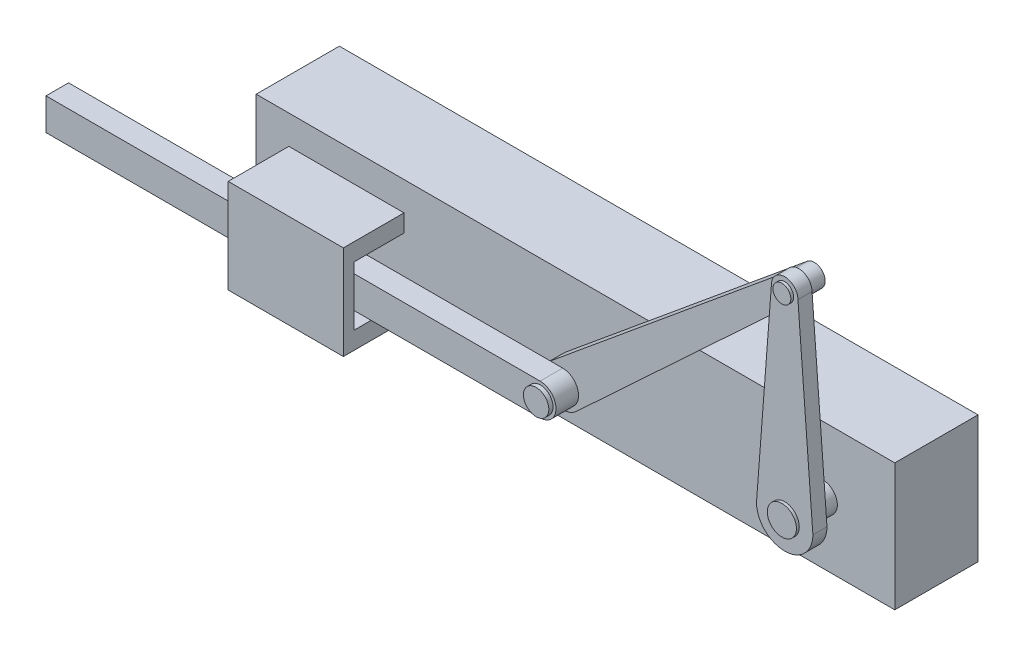
SolidWorks part; units mm, degrees
ref_plane "前视基准面" through (0, 0, 0) normal (0, 0, 1) x (1, 0, 0)
ref_plane "上视基准面" through (0, 0, 0) normal (0, 1, 0) x (1, 0, 0)
ref_plane "右视基准面" through (0, 0, 0) normal (1, 0, 0) x (0, 0, -1)
sketch "草图1" plane through (0, 0, 0) normal (0, 0, 1) x (1, 0, 0)
  line L1 (-43.2595, 0) -> (71.7598, 0)
  line L2 (-43.2595, 0) -> (-43.2595, -22.9274)
  line L3 (-43.2595, -22.9274) -> (71.7598, -22.9274)
  line L4 (71.7598, 0) -> (71.7598, -22.9274)
extrude "凸台-拉伸1" add sketch "草图1" along normal blind 14.986
sketch "草图2" plane through (0, 0, 14.986) normal (0, 0, 1) x (1, 0, 0)
  circle A0 centre (58.7859, -11.7435) radius 2.6281
extrude "凸台-拉伸2" add sketch "草图2" along normal blind 7.366
ref_plane "基准面1" through (0, 0, 21.844) normal (0, 0, 1) x (1, 0, 0)
sketch "草图3" plane through (0, 0, 21.844) normal (0, 0, 1) x (1, 0, 0)
  line L0 (53.7065, -11.7435) -> (56.4009, 23.5958)
  line L1 (63.8654, -11.7435) -> (61.171, 23.5958)
  arc A0 (53.7652, -10.9734) -> (63.8067, -10.9734) centre (58.7859, -11.7435) ccw
  arc A1 (61.171, 23.5958) -> (56.4009, 23.5958) centre (58.7859, 23.5958) ccw
extrude "凸台-拉伸3" add sketch "草图3" against normal blind 2.54 contours L1 A1 L0 A0
sketch "草图5" plane through (0, 0, 19.304) normal (0, 0, -1) x (-1, 0, 0)
  line L0 (-57.5365, 25.1089) -> (-13.9492, -10.8833)
  line L1 (-18.7214, -16.3288) -> (-60.122, 22.1586)
  arc A0 (-57.5365, 25.1089) -> (-60.122, 22.1586) centre (-58.7859, 23.5958) ccw
  arc A1 (-18.7214, -16.3288) -> (-13.9492, -10.8833) centre (-16.2554, -13.6761) ccw
extrude "凸台-拉伸4" add sketch "草图5" along normal blind 2.794
sketch "草图6" plane through (0, 0, 21.844) normal (0, 0, 1) x (1, 0, 0)
  circle A0 centre (58.7859, 23.5958) radius 1.6113
extrude "凸台-拉伸5" add sketch "草图6" along normal blind 0.508
sketch "草图7" plane through (0, 0, 19.304) normal (0, 0, 1) x (1, 0, 0)
  line L1 (16.2554, -10.8075) -> (-72.7333, -10.8075)
  line L3 (16.2554, -16.5447) -> (-72.7333, -16.5447)
  line L4 (-72.7333, -10.8075) -> (-72.7333, -16.5447)
  arc A0 (16.2554, -16.5447) -> (16.2554, -10.8075) centre (16.2554, -13.6761) ccw
extrude "凸台-拉伸6" add sketch "草图7" along normal blind 4.064 contours L1 L4 L3 A0
sketch "草图8" plane through (0, 0, 14.986) normal (0, 0, 1) x (1, 0, 0)
  line L0 (-72.7333, -13.6761) -> (22.4334, -13.6761) construction
  line L1 (-72.7333, -10.8075) -> (-72.7333, -16.5447) construction
  line L2 (-16.6339, -22.1522) -> (-16.6339, -19.0042)
  line L3 (-37.3784, -5.1999) -> (-16.6339, -5.1999)
  line L4 (-37.3784, -5.1999) -> (-37.3784, -8.3479)
  line L5 (-37.3784, -8.3479) -> (-16.6339, -8.3479)
  line L6 (-16.6339, -5.1999) -> (-16.6339, -8.3479)
  line L7 (-37.3784, -19.0042) -> (-16.6339, -19.0042)
  line L8 (-37.3784, -22.1522) -> (-37.3784, -19.0042)
  line L9 (-37.3784, -22.1522) -> (-16.6339, -22.1522)
extrude "凸台-拉伸7" add sketch "草图8" along normal blind 10.922
sketch "草图9" plane through (0, -8.3479, 0) normal (0, -1, 0) x (1, 0, 0)
  line L0 (-16.6339, 25.908) -> (-16.6339, 14.986) construction
  line L1 (-37.3784, 25.908) -> (-16.6339, 25.908)
  line L2 (-37.3784, 25.908) -> (-37.3784, 24.0036)
  line L3 (-37.3784, 24.0036) -> (-16.6339, 24.0036)
  line L4 (-16.6339, 25.908) -> (-16.6339, 24.0036)
extrude "凸台-拉伸8" add sketch "草图9" along normal blind 10.922
sketch "草图10" plane through (0, 0, 23.368) normal (0, 0, 1) x (1, 0, 0)
  circle A0 centre (16.3029, -13.6695) radius 2.2856
extrude "凸台-拉伸9" add sketch "草图10" along normal blind 0.762
sketch "草图11" plane through (0, 0, 0) normal (0, 0, -1) x (-1, 0, 0)
  circle A0 centre (-59.4451, -13.3537) radius 1.572
extrude "凸台-拉伸10" add sketch "草图11" along normal blind 3.302
sketch "草图12" plane through (0, 0, -3.302) normal (0, 0, -1) x (-1, 0, 0)
  line L1 (-67.8813, -5.7378) -> (-50.306, -5.7378)
  line L2 (-67.8813, -5.7378) -> (-67.8813, -22.4929)
  line L3 (-67.8813, -22.4929) -> (-50.306, -22.4929)
  line L4 (-50.306, -5.7378) -> (-50.306, -22.4929)
extrude "凸台-拉伸11" add sketch "草图12" along normal blind 13.462
sketch "草图13" plane through (0, 0, 16.51) normal (0, 0, -1) x (-1, 0, 0)
  circle A0 centre (-58.8502, 23.5206) radius 1.3313
  circle A1 centre (-58.8502, 23.5206) radius 1.0773
  dimension "D1" = 0.254
extrude "切除-拉伸1" cut sketch "草图13" against normal blind 0.762 contours A0 A1
sketch "草图14" plane through (67.8813, 0, 0) normal (1, 0, 0) x (0, 0, -1)
  line L1 (3.2549, -3.7083) -> (20.0893, -3.7083)
  line L2 (3.2549, -3.7083) -> (3.2549, -24.1354)
  line L3 (3.2549, -24.1354) -> (20.0893, -24.1354)
  line L4 (20.0893, -3.7083) -> (20.0893, -24.1354)
extrude "切除-拉伸2" cut sketch "草图14" against normal blind 28.194
